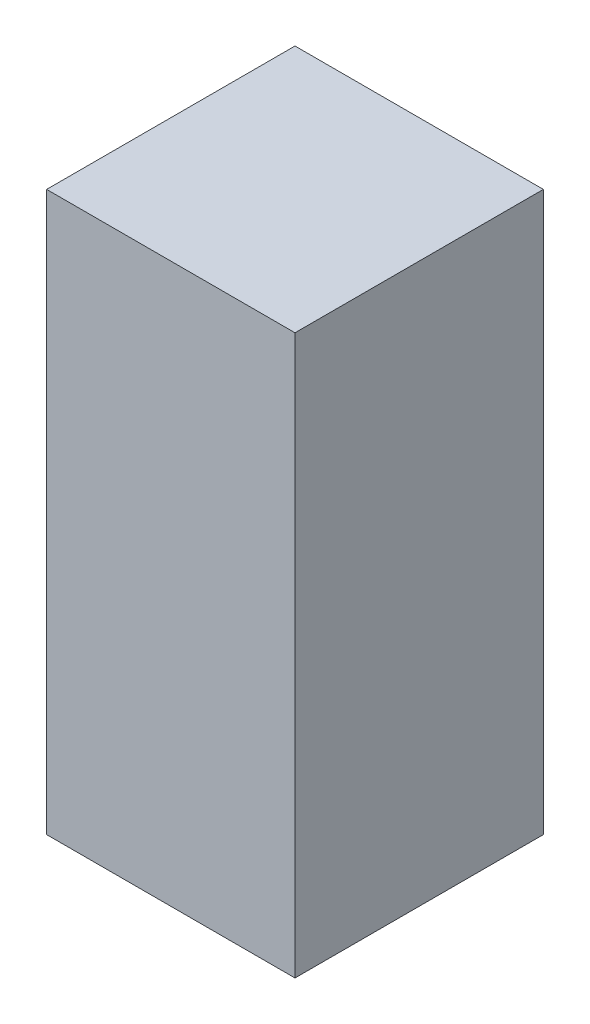
SolidWorks part; units mm, degrees
ref_plane "Front Plane" through (0, 0, 0) normal (0, 0, 1) x (1, 0, 0)
ref_plane "Top Plane" through (0, 0, 0) normal (0, 1, 0) x (1, 0, 0)
ref_plane "Right Plane" through (0, 0, 0) normal (1, 0, 0) x (0, 0, -1)
sketch "Sketch2" plane through (0, 0, 0) normal (0, 1, 0) x (1, 0, 0)
  line L1 (0, 0) -> (609.6, 0)
  line L2 (0, 0) -> (0, 609.6)
  line L3 (0, 609.6) -> (609.6, 609.6)
  line L4 (609.6, 0) -> (609.6, 609.6)
  dimension "D1" = 609.6
extrude "Boss-Extrude1" add sketch "Sketch2" along normal blind 1371.6
